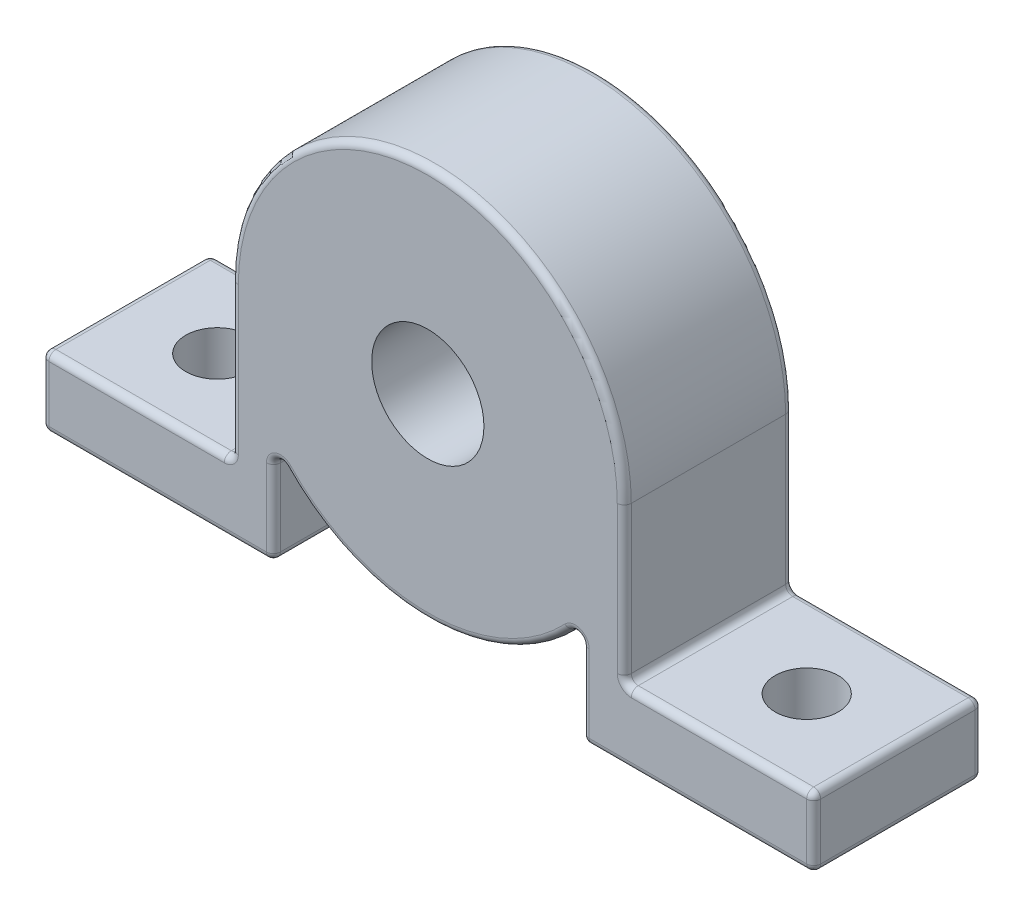
SolidWorks part; units mm, degrees
ref_plane "前视基准面" through (0, 0, 0) normal (0, 0, 1) x (1, 0, 0)
ref_plane "上视基准面" through (0, 0, 0) normal (0, 1, 0) x (1, 0, 0)
ref_plane "右视基准面" through (0, 0, 0) normal (1, 0, 0) x (0, 0, -1)
sketch "草图1" plane through (0, 0, 0) normal (0, 0, 1) x (1, 0, 0)
  line L0 (-27.5, 0) -> (-11, 0)
  line L1 (-27.5, 0) -> (-27.5, 5)
  line L2 (-14, 16) -> (-14, 5)
  line L3 (-14, 5) -> (-27.5, 5)
  line L4 (-11, 0) -> (-11, 7.3397)
  line L5 (27.5, 0) -> (27.5, 5)
  line L6 (0, 33.6171) -> (0, 24.4172) construction
  line L7 (11, 0) -> (11, 7.3397)
  line L8 (27.5, 0) -> (27.5, 5)
  line L9 (14, 5) -> (27.5, 5)
  line L10 (14, 16) -> (14, 5)
  line L11 (11, 0) -> (27.5, 0)
  circle A0 centre (0, 16) radius 14
  circle A1 centre (0, 16) radius 4
  circle A2 centre (0, 16) radius 13
  circle A3 centre (0, 16) radius 5
  point P6 (0, 30)
  point P12 (-14, 0)
  point P13 (-11, 0)
  point P17 (-21, 5)
  point P22 (21, 5)
  dimension "D1" = 16
  dimension "D3" = 55
  dimension "D2" = 30
  dimension "D4" = 5
  dimension "D5" = 3
  dimension "D6" = 6.5
extrude "凸台-拉伸6" add sketch "草图1" along normal mid plane 12
fillet "圆角2" radius 0.5 34 edges at (-11, 7.3397, 0) (11, 7.3397, 0) (-11, 0, 0) (11, 0, 0) (19.25, 0, -6) (19.25, 0, 6) (11, 3.6699, -6) (11, 3.6699, 6) (0, 2, -6) (0, 2, 6) (-11, 3.6699, -6) (-11, 3.6699, 6) (-19.25, 0, -6) (-19.25, 0, 6) (-27.5, 2.5, -6) (-27.5, 2.5, 6) (-27.5, 0, 0) (27.5, 2.5, -6) (27.5, 2.5, 6) (27.5, 0, 0) (27.5, 5, 0) (20.75, 5, -6) (20.75, 5, 6) (14, 5, 0) (14, 10.5, -6) (14, 10.5, 6) (0, 30, -6) (0, 30, 6) (-14, 10.5, -6) (-14, 10.5, 6) (-14, 5, 0) (-20.75, 5, -6) (-20.75, 5, 6) (-27.5, 5, 0)
sketch "草图5" plane through (0, 5, 0) normal (0, 1, 0) x (1, 0, 0)
  line L0 (27.5, 5.5) -> (27.5, -5.5) construction
  circle A0 centre (21, 0) radius 2.25
  point P8 (21, 0)
  dimension "D1" = 6.5
extrude "切除-拉伸1" cut sketch "草图5" against normal up to next contours A0
sketch "草图8" plane through (0, 5, 0) normal (0, 1, 0) x (1, 0, 0)
  line L0 (-27.5, -5.5) -> (-27.5, 5.5) construction
  circle A0 centre (-21, 0) radius 2.25
  point P8 (-21, 0)
  dimension "D1" = 6.5
extrude "切除-拉伸2" cut sketch "草图8" against normal up to next contours A0
